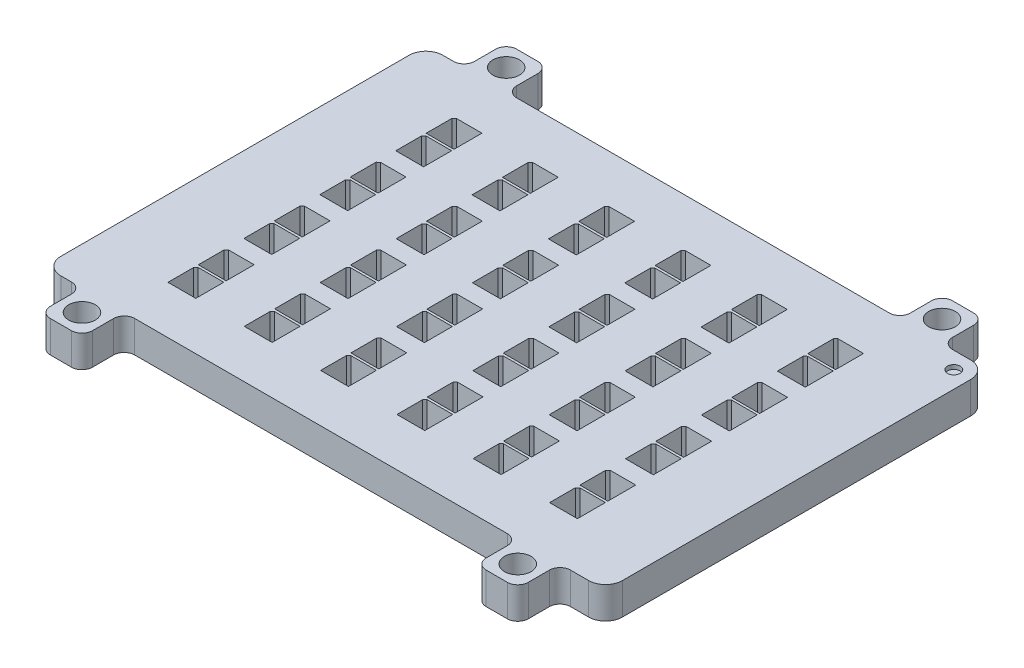
SolidWorks part; units mm, degrees
ref_plane "Front Plane" through (0, 0, 0) normal (0, 0, 1) x (1, 0, 0)
ref_plane "Top Plane" through (0, 0, 0) normal (0, 1, 0) x (1, 0, 0)
ref_plane "Right Plane" through (0, 0, 0) normal (1, 0, 0) x (0, 0, -1)
sketch "Sketch1" plane through (0, 0, 0) normal (0, 1, 0) x (1, 0, 0)
  line L1 (0, 0) -> (157.864, 0)
  line L2 (0, 0) -> (0, -90.551)
  line L3 (0, -90.551) -> (157.864, -90.551)
  line L4 (157.864, 0) -> (157.864, -90.551)
  dimension "D1" = 157.864
  dimension "D2" = 90.551
extrude "Boss-Extrude1" add sketch "Sketch1" along normal blind 24.5
sketch "Sketch39" plane through (0, 24.5, 0) normal (0, 1, 0) x (1, 0, 0)
  line L0 (37.0058, -18.5555) -> (30.949, -18.5555)
  line L1 (30.949, -18.5555) -> (30.4082, -19.0884)
  line L2 (30.4082, -19.0884) -> (30.4082, -25.1854)
  line L3 (30.4082, -25.1854) -> (37.0058, -25.1854)
  line L4 (37.0058, -18.5555) -> (37.0058, -25.1854)
  line L5 (30.4082, -25.1854) -> (37.0058, -18.5555) construction
  line L6 (55.0958, -11.3656) -> (49.039, -11.3656)
  line L7 (49.039, -11.3656) -> (48.4982, -11.8986)
  line L8 (48.4982, -11.8986) -> (48.4982, -17.9955)
  line L9 (48.4982, -17.9955) -> (55.0958, -17.9955)
  line L10 (55.0958, -11.3656) -> (55.0958, -17.9955)
  line L11 (48.4982, -17.9955) -> (55.0958, -11.3656) construction
  line L12 (73.1858, -11.3656) -> (67.129, -11.3656)
  line L13 (67.129, -11.3656) -> (66.5882, -11.8986)
  line L14 (66.5882, -11.8986) -> (66.5882, -17.9955)
  line L15 (66.5882, -17.9955) -> (73.1858, -17.9955)
  line L16 (73.1858, -11.3656) -> (73.1858, -17.9955)
  line L17 (66.5882, -17.9955) -> (73.1858, -11.3656) construction
  line L18 (91.2758, -11.3656) -> (85.219, -11.3656)
  line L19 (85.219, -11.3656) -> (84.6782, -11.8986)
  line L20 (84.6782, -11.8986) -> (84.6782, -17.9955)
  line L21 (84.6782, -17.9955) -> (91.2758, -17.9955)
  line L22 (91.2758, -11.3656) -> (91.2758, -17.9955)
  line L23 (84.6782, -17.9955) -> (91.2758, -11.3656) construction
  line L24 (109.3658, -11.3656) -> (103.309, -11.3656)
  line L25 (103.309, -11.3656) -> (102.7682, -11.8986)
  line L26 (102.7682, -11.8986) -> (102.7682, -17.9955)
  line L27 (102.7682, -17.9955) -> (109.3658, -17.9955)
  line L28 (109.3658, -11.3656) -> (109.3658, -17.9955)
  line L29 (102.7682, -17.9955) -> (109.3658, -11.3656) construction
  line L30 (127.4558, -11.3656) -> (121.399, -11.3656)
  line L31 (121.399, -11.3656) -> (120.8582, -11.8986)
  line L32 (120.8582, -11.8986) -> (120.8582, -17.9955)
  line L33 (120.8582, -17.9955) -> (127.4558, -17.9955)
  line L34 (127.4558, -11.3656) -> (127.4558, -17.9955)
  line L35 (120.8582, -17.9955) -> (127.4558, -11.3656) construction
  line L36 (55.0958, -29.3656) -> (49.039, -29.3656)
  line L37 (49.039, -29.3656) -> (48.4982, -29.8986)
  line L38 (48.4982, -29.8986) -> (48.4982, -35.9955)
  line L39 (48.4982, -35.9955) -> (55.0958, -35.9955)
  line L40 (55.0958, -29.3656) -> (55.0958, -35.9955)
  line L41 (48.4982, -35.9955) -> (55.0958, -29.3656) construction
  line L42 (73.1858, -29.3656) -> (67.129, -29.3656)
  line L43 (67.129, -29.3656) -> (66.5882, -29.8986)
  line L44 (66.5882, -29.8986) -> (66.5882, -35.9955)
  line L45 (66.5882, -35.9955) -> (73.1858, -35.9955)
  line L46 (73.1858, -29.3656) -> (73.1858, -35.9955)
  line L47 (66.5882, -35.9955) -> (73.1858, -29.3656) construction
  line L48 (91.2758, -29.3656) -> (85.219, -29.3656)
  line L49 (85.219, -29.3656) -> (84.6782, -29.8986)
  line L50 (84.6782, -29.8986) -> (84.6782, -35.9955)
  line L51 (84.6782, -35.9955) -> (91.2758, -35.9955)
  line L52 (91.2758, -29.3656) -> (91.2758, -35.9955)
  line L53 (84.6782, -35.9955) -> (91.2758, -29.3656) construction
  line L54 (109.3658, -29.3656) -> (103.309, -29.3656)
  line L55 (103.309, -29.3656) -> (102.7682, -29.8986)
  line L56 (102.7682, -29.8986) -> (102.7682, -35.9955)
  line L57 (102.7682, -35.9955) -> (109.3658, -35.9955)
  line L58 (109.3658, -29.3656) -> (109.3658, -35.9955)
  line L59 (102.7682, -35.9955) -> (109.3658, -29.3656) construction
  line L60 (127.4558, -29.3656) -> (121.399, -29.3656)
  line L61 (121.399, -29.3656) -> (120.8582, -29.8986)
  line L62 (120.8582, -29.8986) -> (120.8582, -35.9955)
  line L63 (120.8582, -35.9955) -> (127.4558, -35.9955)
  line L64 (127.4558, -29.3656) -> (127.4558, -35.9955)
  line L65 (120.8582, -35.9955) -> (127.4558, -29.3656) construction
  line L66 (55.0958, -47.3656) -> (49.039, -47.3656)
  line L67 (49.039, -47.3656) -> (48.4982, -47.8986)
  line L68 (48.4982, -47.8986) -> (48.4982, -53.9955)
  line L69 (48.4982, -53.9955) -> (55.0958, -53.9955)
  line L70 (55.0958, -47.3656) -> (55.0958, -53.9955)
  line L71 (48.4982, -53.9955) -> (55.0958, -47.3656) construction
  line L72 (73.1858, -47.3656) -> (67.129, -47.3656)
  line L73 (67.129, -47.3656) -> (66.5882, -47.8986)
  line L74 (66.5882, -47.8986) -> (66.5882, -53.9955)
  line L75 (66.5882, -53.9955) -> (73.1858, -53.9955)
  line L76 (73.1858, -47.3656) -> (73.1858, -53.9955)
  line L77 (66.5882, -53.9955) -> (73.1858, -47.3656) construction
  line L78 (91.2758, -47.3656) -> (85.219, -47.3656)
  line L79 (85.219, -47.3656) -> (84.6782, -47.8986)
  line L80 (84.6782, -47.8986) -> (84.6782, -53.9955)
  line L81 (84.6782, -53.9955) -> (91.2758, -53.9955)
  line L82 (91.2758, -47.3656) -> (91.2758, -53.9955)
  line L83 (84.6782, -53.9955) -> (91.2758, -47.3656) construction
  line L84 (109.3658, -47.3656) -> (103.309, -47.3656)
  line L85 (103.309, -47.3656) -> (102.7682, -47.8986)
  line L86 (102.7682, -47.8986) -> (102.7682, -53.9955)
  line L87 (102.7682, -53.9955) -> (109.3658, -53.9955)
  line L88 (109.3658, -47.3656) -> (109.3658, -53.9955)
  line L89 (102.7682, -53.9955) -> (109.3658, -47.3656) construction
  line L90 (127.4558, -47.3656) -> (121.399, -47.3656)
  line L91 (121.399, -47.3656) -> (120.8582, -47.8986)
  line L92 (120.8582, -47.8986) -> (120.8582, -53.9955)
  line L93 (120.8582, -53.9955) -> (127.4558, -53.9955)
  line L94 (127.4558, -47.3656) -> (127.4558, -53.9955)
  line L95 (120.8582, -53.9955) -> (127.4558, -47.3656) construction
  line L96 (55.0958, -65.3656) -> (49.039, -65.3656)
  line L97 (49.039, -65.3656) -> (48.4982, -65.8986)
  line L98 (48.4982, -65.8986) -> (48.4982, -71.9955)
  line L99 (48.4982, -71.9955) -> (55.0958, -71.9955)
  line L100 (55.0958, -65.3656) -> (55.0958, -71.9955)
  line L101 (48.4982, -71.9955) -> (55.0958, -65.3656) construction
  line L102 (73.1858, -65.3656) -> (67.129, -65.3656)
  line L103 (67.129, -65.3656) -> (66.5882, -65.8986)
  line L104 (66.5882, -65.8986) -> (66.5882, -71.9955)
  line L105 (66.5882, -71.9955) -> (73.1858, -71.9955)
  line L106 (73.1858, -65.3656) -> (73.1858, -71.9955)
  line L107 (66.5882, -71.9955) -> (73.1858, -65.3656) construction
  line L108 (91.2758, -65.3656) -> (85.219, -65.3656)
  line L109 (85.219, -65.3656) -> (84.6782, -65.8986)
  line L110 (84.6782, -65.8986) -> (84.6782, -71.9955)
  line L111 (84.6782, -71.9955) -> (91.2758, -71.9955)
  line L112 (91.2758, -65.3656) -> (91.2758, -71.9955)
  line L113 (84.6782, -71.9955) -> (91.2758, -65.3656) construction
  line L114 (109.3658, -65.3656) -> (103.309, -65.3656)
  line L115 (103.309, -65.3656) -> (102.7682, -65.8986)
  line L116 (102.7682, -65.8986) -> (102.7682, -71.9955)
  line L117 (102.7682, -71.9955) -> (109.3658, -71.9955)
  line L118 (109.3658, -65.3656) -> (109.3658, -71.9955)
  line L119 (102.7682, -71.9955) -> (109.3658, -65.3656) construction
  line L120 (127.4558, -65.3656) -> (121.399, -65.3656)
  line L121 (121.399, -65.3656) -> (120.8582, -65.8986)
  line L122 (120.8582, -65.8986) -> (120.8582, -71.9955)
  line L123 (120.8582, -71.9955) -> (127.4558, -71.9955)
  line L124 (127.4558, -65.3656) -> (127.4558, -71.9955)
  line L125 (120.8582, -71.9955) -> (127.4558, -65.3656) construction
  line L126 (37.0058, -29.3656) -> (30.949, -29.3656)
  line L127 (30.949, -29.3656) -> (30.4082, -29.8986)
  line L128 (30.4082, -29.8986) -> (30.4082, -35.9955)
  line L129 (30.4082, -35.9955) -> (37.0058, -35.9955)
  line L130 (37.0058, -29.3656) -> (37.0058, -35.9955)
  line L131 (30.4082, -35.9955) -> (37.0058, -29.3656) construction
  line L132 (37.0058, -47.3656) -> (30.949, -47.3656)
  line L133 (30.949, -47.3656) -> (30.4082, -47.8986)
  line L134 (30.4082, -47.8986) -> (30.4082, -53.9955)
  line L135 (30.4082, -53.9955) -> (37.0058, -53.9955)
  line L136 (37.0058, -47.3656) -> (37.0058, -53.9955)
  line L137 (30.4082, -53.9955) -> (37.0058, -47.3656) construction
  line L138 (37.0058, -65.3656) -> (30.949, -65.3656)
  line L139 (30.949, -65.3656) -> (30.4082, -65.8986)
  line L140 (30.4082, -65.8986) -> (30.4082, -71.9955)
  line L141 (30.4082, -71.9955) -> (37.0058, -71.9955)
  line L142 (37.0058, -65.3656) -> (37.0058, -71.9955)
  line L143 (30.4082, -71.9955) -> (37.0058, -65.3656) construction
  line L144 (37.0058, -11.3656) -> (30.949, -11.3656)
  line L145 (30.949, -11.3656) -> (30.4082, -11.8986)
  line L146 (30.4082, -11.8986) -> (30.4082, -17.9955)
  line L147 (30.4082, -17.9955) -> (37.0058, -17.9955)
  line L148 (37.0058, -11.3656) -> (37.0058, -17.9955)
  line L149 (30.4082, -17.9955) -> (37.0058, -11.3656) construction
  line L150 (48.4982, -25.1854) -> (55.0958, -25.1854)
  line L151 (55.0958, -18.5555) -> (55.0958, -25.1854)
  line L152 (55.0958, -18.5555) -> (49.039, -18.5555)
  line L153 (49.039, -18.5555) -> (48.4982, -19.0884)
  line L154 (48.4982, -19.0884) -> (48.4982, -25.1854)
  line L155 (48.4982, -25.1854) -> (55.0958, -18.5555) construction
  line L156 (66.5882, -25.1854) -> (73.1858, -25.1854)
  line L157 (73.1858, -18.5555) -> (73.1858, -25.1854)
  line L158 (73.1858, -18.5555) -> (67.129, -18.5555)
  line L159 (67.129, -18.5555) -> (66.5882, -19.0884)
  line L160 (66.5882, -19.0884) -> (66.5882, -25.1854)
  line L161 (66.5882, -25.1854) -> (73.1858, -18.5555) construction
  line L162 (84.6782, -25.1854) -> (91.2758, -25.1854)
  line L163 (91.2758, -18.5555) -> (91.2758, -25.1854)
  line L164 (91.2758, -18.5555) -> (85.219, -18.5555)
  line L165 (85.219, -18.5555) -> (84.6782, -19.0884)
  line L166 (84.6782, -19.0884) -> (84.6782, -25.1854)
  line L167 (84.6782, -25.1854) -> (91.2758, -18.5555) construction
  line L168 (102.7682, -25.1854) -> (109.3658, -25.1854)
  line L169 (109.3658, -18.5555) -> (109.3658, -25.1854)
  line L170 (109.3658, -18.5555) -> (103.309, -18.5555)
  line L171 (103.309, -18.5555) -> (102.7682, -19.0884)
  line L172 (102.7682, -19.0884) -> (102.7682, -25.1854)
  line L173 (102.7682, -25.1854) -> (109.3658, -18.5555) construction
  line L174 (120.8582, -25.1854) -> (127.4558, -25.1854)
  line L175 (127.4558, -18.5555) -> (127.4558, -25.1854)
  line L176 (127.4558, -18.5555) -> (121.399, -18.5555)
  line L177 (121.399, -18.5555) -> (120.8582, -19.0884)
  line L178 (120.8582, -19.0884) -> (120.8582, -25.1854)
  line L179 (120.8582, -25.1854) -> (127.4558, -18.5555) construction
  line L180 (48.4982, -43.1854) -> (55.0958, -43.1854)
  line L181 (55.0958, -36.5555) -> (55.0958, -43.1854)
  line L182 (55.0958, -36.5555) -> (49.039, -36.5555)
  line L183 (49.039, -36.5555) -> (48.4982, -37.0884)
  line L184 (48.4982, -37.0884) -> (48.4982, -43.1854)
  line L185 (48.4982, -43.1854) -> (55.0958, -36.5555) construction
  line L186 (66.5882, -43.1854) -> (73.1858, -43.1854)
  line L187 (73.1858, -36.5555) -> (73.1858, -43.1854)
  line L188 (73.1858, -36.5555) -> (67.129, -36.5555)
  line L189 (67.129, -36.5555) -> (66.5882, -37.0884)
  line L190 (66.5882, -37.0884) -> (66.5882, -43.1854)
  line L191 (66.5882, -43.1854) -> (73.1858, -36.5555) construction
  line L192 (84.6782, -43.1854) -> (91.2758, -43.1854)
  line L193 (91.2758, -36.5555) -> (91.2758, -43.1854)
  line L194 (91.2758, -36.5555) -> (85.219, -36.5555)
  line L195 (85.219, -36.5555) -> (84.6782, -37.0884)
  line L196 (84.6782, -37.0884) -> (84.6782, -43.1854)
  line L197 (84.6782, -43.1854) -> (91.2758, -36.5555) construction
  line L198 (102.7682, -43.1854) -> (109.3658, -43.1854)
  line L199 (109.3658, -36.5555) -> (109.3658, -43.1854)
  line L200 (109.3658, -36.5555) -> (103.309, -36.5555)
  line L201 (103.309, -36.5555) -> (102.7682, -37.0884)
  line L202 (102.7682, -37.0884) -> (102.7682, -43.1854)
  line L203 (102.7682, -43.1854) -> (109.3658, -36.5555) construction
  line L204 (120.8582, -43.1854) -> (127.4558, -43.1854)
  line L205 (127.4558, -36.5555) -> (127.4558, -43.1854)
  line L206 (127.4558, -36.5555) -> (121.399, -36.5555)
  line L207 (121.399, -36.5555) -> (120.8582, -37.0884)
  line L208 (120.8582, -37.0884) -> (120.8582, -43.1854)
  line L209 (120.8582, -43.1854) -> (127.4558, -36.5555) construction
  line L210 (48.4982, -61.1854) -> (55.0958, -61.1854)
  line L211 (55.0958, -54.5555) -> (55.0958, -61.1854)
  line L212 (55.0958, -54.5555) -> (49.039, -54.5555)
  line L213 (49.039, -54.5555) -> (48.4982, -55.0884)
  line L214 (48.4982, -55.0884) -> (48.4982, -61.1854)
  line L215 (48.4982, -61.1854) -> (55.0958, -54.5555) construction
  line L216 (66.5882, -61.1854) -> (73.1858, -61.1854)
  line L217 (73.1858, -54.5555) -> (73.1858, -61.1854)
  line L218 (73.1858, -54.5555) -> (67.129, -54.5555)
  line L219 (67.129, -54.5555) -> (66.5882, -55.0884)
  line L220 (66.5882, -55.0884) -> (66.5882, -61.1854)
  line L221 (66.5882, -61.1854) -> (73.1858, -54.5555) construction
  line L222 (84.6782, -61.1854) -> (91.2758, -61.1854)
  line L223 (91.2758, -54.5555) -> (91.2758, -61.1854)
  line L224 (91.2758, -54.5555) -> (85.219, -54.5555)
  line L225 (85.219, -54.5555) -> (84.6782, -55.0884)
  line L226 (84.6782, -55.0884) -> (84.6782, -61.1854)
  line L227 (84.6782, -61.1854) -> (91.2758, -54.5555) construction
  line L228 (102.7682, -61.1854) -> (109.3658, -61.1854)
  line L229 (109.3658, -54.5555) -> (109.3658, -61.1854)
  line L230 (109.3658, -54.5555) -> (103.309, -54.5555)
  line L231 (103.309, -54.5555) -> (102.7682, -55.0884)
  line L232 (102.7682, -55.0884) -> (102.7682, -61.1854)
  line L233 (102.7682, -61.1854) -> (109.3658, -54.5555) construction
  line L234 (120.8582, -61.1854) -> (127.4558, -61.1854)
  line L235 (127.4558, -54.5555) -> (127.4558, -61.1854)
  line L236 (127.4558, -54.5555) -> (121.399, -54.5555)
  line L237 (121.399, -54.5555) -> (120.8582, -55.0884)
  line L238 (120.8582, -55.0884) -> (120.8582, -61.1854)
  line L239 (120.8582, -61.1854) -> (127.4558, -54.5555) construction
  line L240 (48.4982, -79.1854) -> (55.0958, -79.1854)
  line L241 (55.0958, -72.5555) -> (55.0958, -79.1854)
  line L242 (55.0958, -72.5555) -> (49.039, -72.5555)
  line L243 (49.039, -72.5555) -> (48.4982, -73.0884)
  line L244 (48.4982, -73.0884) -> (48.4982, -79.1854)
  line L245 (48.4982, -79.1854) -> (55.0958, -72.5555) construction
  line L246 (66.5882, -79.1854) -> (73.1858, -79.1854)
  line L247 (73.1858, -72.5555) -> (73.1858, -79.1854)
  line L248 (73.1858, -72.5555) -> (67.129, -72.5555)
  line L249 (67.129, -72.5555) -> (66.5882, -73.0884)
  line L250 (66.5882, -73.0884) -> (66.5882, -79.1854)
  line L251 (66.5882, -79.1854) -> (73.1858, -72.5555) construction
  line L252 (84.6782, -79.1854) -> (91.2758, -79.1854)
  line L253 (91.2758, -72.5555) -> (91.2758, -79.1854)
  line L254 (91.2758, -72.5555) -> (85.219, -72.5555)
  line L255 (85.219, -72.5555) -> (84.6782, -73.0884)
  line L256 (84.6782, -73.0884) -> (84.6782, -79.1854)
  line L257 (84.6782, -79.1854) -> (91.2758, -72.5555) construction
  line L258 (102.7682, -79.1854) -> (109.3658, -79.1854)
  line L259 (109.3658, -72.5555) -> (109.3658, -79.1854)
  line L260 (109.3658, -72.5555) -> (103.309, -72.5555)
  line L261 (103.309, -72.5555) -> (102.7682, -73.0884)
  line L262 (102.7682, -73.0884) -> (102.7682, -79.1854)
  line L263 (102.7682, -79.1854) -> (109.3658, -72.5555) construction
  line L264 (120.8582, -79.1854) -> (127.4558, -79.1854)
  line L265 (127.4558, -72.5555) -> (127.4558, -79.1854)
  line L266 (127.4558, -72.5555) -> (121.399, -72.5555)
  line L267 (121.399, -72.5555) -> (120.8582, -73.0884)
  line L268 (120.8582, -73.0884) -> (120.8582, -79.1854)
  line L269 (120.8582, -79.1854) -> (127.4558, -72.5555) construction
  line L270 (30.4082, -43.1854) -> (37.0058, -43.1854)
  line L271 (37.0058, -36.5555) -> (37.0058, -43.1854)
  line L272 (37.0058, -36.5555) -> (30.949, -36.5555)
  line L273 (30.949, -36.5555) -> (30.4082, -37.0884)
  line L274 (30.4082, -37.0884) -> (30.4082, -43.1854)
  line L275 (30.4082, -43.1854) -> (37.0058, -36.5555) construction
  line L276 (30.4082, -61.1854) -> (37.0058, -61.1854)
  line L277 (37.0058, -54.5555) -> (37.0058, -61.1854)
  line L278 (37.0058, -54.5555) -> (30.949, -54.5555)
  line L279 (30.949, -54.5555) -> (30.4082, -55.0884)
  line L280 (30.4082, -55.0884) -> (30.4082, -61.1854)
  line L281 (30.4082, -61.1854) -> (37.0058, -54.5555) construction
  line L282 (30.4082, -79.1854) -> (37.0058, -79.1854)
  line L283 (37.0058, -72.5555) -> (37.0058, -79.1854)
  line L284 (37.0058, -72.5555) -> (30.949, -72.5555)
  line L285 (30.949, -72.5555) -> (30.4082, -73.0884)
  line L286 (30.4082, -73.0884) -> (30.4082, -79.1854)
  line L287 (30.4082, -79.1854) -> (37.0058, -72.5555) construction
  line L288 (127.4558, -25.1854) -> (157.864, -25.1854) construction
  line L289 (30.4082, -79.1854) -> (0, -79.1854) construction
  line L290 (0, 0) -> (0, -90.551) construction
  line L291 (30.4082, -79.1854) -> (30.4082, -90.551) construction
  line L292 (0, -90.551) -> (157.864, -90.551) construction
  line L293 (127.4558, -11.3656) -> (127.4558, 0) construction
  line L294 (157.864, 0) -> (0, 0) construction
  line L295 (127.4558, -11.3656) -> (157.864, -11.3656) construction
  line L296 (157.864, -90.551) -> (157.864, 0) construction
  point P0 (33.707, -21.8704)
  point P2 (33.707, -14.6806)
  point P12 (51.797, -14.6806)
  point P18 (69.887, -14.6806)
  point P24 (87.977, -14.6806)
  point P30 (106.067, -14.6806)
  point P36 (124.157, -14.6806)
  point P42 (51.797, -32.6806)
  point P48 (69.887, -32.6806)
  point P54 (87.977, -32.6806)
  point P60 (106.067, -32.6806)
  point P66 (124.157, -32.6806)
  point P72 (51.797, -50.6806)
  point P78 (69.887, -50.6806)
  point P84 (87.977, -50.6806)
  point P90 (106.067, -50.6806)
  point P96 (124.157, -50.6806)
  point P102 (51.797, -68.6806)
  point P108 (69.887, -68.6806)
  point P114 (87.977, -68.6806)
  point P120 (106.067, -68.6806)
  point P126 (124.157, -68.6806)
  point P132 (33.707, -32.6806)
  point P138 (33.707, -50.6806)
  point P144 (33.707, -68.6806)
  point P153 (51.797, -21.8704)
  point P159 (69.887, -21.8704)
  point P165 (87.977, -21.8704)
  point P171 (106.067, -21.8704)
  point P177 (124.157, -21.8704)
  point P183 (51.797, -39.8704)
  point P189 (69.887, -39.8704)
  point P195 (87.977, -39.8704)
  point P201 (106.067, -39.8704)
  point P207 (124.157, -39.8704)
  point P213 (51.797, -57.8704)
  point P219 (69.887, -57.8704)
  point P225 (87.977, -57.8704)
  point P231 (106.067, -57.8704)
  point P237 (124.157, -57.8704)
  point P243 (51.797, -75.8704)
  point P249 (69.887, -75.8704)
  point P255 (87.977, -75.8704)
  point P261 (106.067, -75.8704)
  point P267 (124.157, -75.8704)
  point P273 (33.707, -39.8704)
  point P279 (33.707, -57.8704)
  point P285 (33.707, -75.8704)
  dimension "D2" = 6.0568
  dimension "D3" = 6.0969
  dimension "D4" = 6.5976
  dimension "D5" = 6.6299
  dimension "D6" = 0.7593
  dimension "D7" = 6
  dimension "D8" = 4
  dimension "D9" = 0.56
  dimension "D10" = 6.0568
  dimension "D11" = 6.0969
  dimension "D12" = 6.6299
  dimension "D13" = 6.5976
  dimension "D14" = 0.7593
  dimension "D15" = 6
  dimension "D16" = 4
extrude "Cut-Extrude30" cut sketch "Sketch39" against normal up to surface (24.5 mm away) up to face at (78.932, 0, 45.2755)
sketch "Sketch7" plane through (0, 0, 0) normal (0, -1, 0) x (1, 0, 0)
  line L0 (124.157, 18.2755) -> (157.864, 18.2755) construction
  line L1 (157.864, 90.551) -> (157.864, 0) construction
  line L2 (124.157, 18.2755) -> (124.157, 0) construction
  line L3 (157.864, 0) -> (0, 0) construction
  line L4 (33.707, 18.2755) -> (0, 18.2755) construction
  line L5 (0, 0) -> (0, 90.551) construction
  line L6 (33.707, 72.2755) -> (33.707, 90.551) construction
  line L7 (0, 90.551) -> (157.864, 90.551) construction
  line L8 (33.707, 72.2755) -> (33.707, 90.551) construction
  circle A0 centre (33.707, 72.2755) radius 7.75
  circle A2 centre (51.797, 72.2755) radius 7.75
  circle A3 centre (69.887, 72.2755) radius 7.75
  circle A4 centre (87.977, 72.2755) radius 7.75
  circle A5 centre (106.067, 72.2755) radius 7.75
  circle A6 centre (124.157, 72.2755) radius 7.75
  circle A7 centre (51.797, 54.2755) radius 7.75
  circle A8 centre (69.887, 54.2755) radius 7.75
  circle A9 centre (87.977, 54.2755) radius 7.75
  circle A10 centre (106.067, 54.2755) radius 7.75
  circle A11 centre (124.157, 54.2755) radius 7.75
  circle A12 centre (51.797, 36.2755) radius 7.75
  circle A13 centre (69.887, 36.2755) radius 7.75
  circle A14 centre (87.977, 36.2755) radius 7.75
  circle A15 centre (106.067, 36.2755) radius 7.75
  circle A16 centre (124.157, 36.2755) radius 7.75
  circle A17 centre (51.797, 18.2755) radius 7.75
  circle A18 centre (69.887, 18.2755) radius 7.75
  circle A19 centre (87.977, 18.2755) radius 7.75
  circle A20 centre (106.067, 18.2755) radius 7.75
  circle A21 centre (124.157, 18.2755) radius 7.75
  circle A22 centre (33.707, 54.2755) radius 7.75
  circle A23 centre (33.707, 36.2755) radius 7.75
  circle A24 centre (33.707, 18.2755) radius 7.75
  dimension "D1" = 15.5
  dimension "D6" = 18
  dimension "D3" = 18.09
  dimension "D4" = 18
  dimension "D5" = 18.09
  dimension "D7" = 6
  dimension "D8" = 4
extrude "Cut-Extrude5" cut sketch "Sketch7" along normal blind 17 from surface at -24.5 starting at face at (33.1554, 24.5, 75.314)
sketch "Sketch23" plane through (0, 24.5, 0) normal (0, 1, 0) x (1, 0, 0)
  line L0 (0, -90.551) -> (157.864, -90.551) construction
  line L1 (143.5751, -88.6374) -> (14.2889, -88.6374)
  line L2 (143.5751, -88.6374) -> (143.5751, -1.9136)
  line L3 (143.5751, -1.9136) -> (14.2889, -1.9136)
  line L4 (14.2889, -88.6374) -> (14.2889, -1.9136)
  line L5 (134.6751, -82.6374) -> (23.1889, -82.6374)
  line L6 (134.6751, -82.6374) -> (134.6751, -7.9136)
  line L7 (134.6751, -7.9136) -> (23.1889, -7.9136)
  line L8 (23.1889, -82.6374) -> (23.1889, -7.9136)
  line L9 (157.864, -90.551) -> (157.864, 0) construction
  line L10 (157.864, 0) -> (0, 0) construction
  line L11 (0, 0) -> (0, -90.551) construction
  point P8 (157.864, -45.2755)
  point P17 (0, -45.2755)
  dimension "D1" = 129.2861
  dimension "D2" = 8.9
  dimension "D3" = 8.9
  dimension "D4" = 6
  dimension "D5" = 6
  dimension "D6" = 14.2889
  dimension "D8" = 1.9136
  dimension "D9" = 86.7238
  dimension "D10" = 1.9136
  dimension "D11" = 14.2889
extrude "Cut-Extrude21" cut sketch "Sketch23" against normal blind 4.5
fillet "Fillet7" radius 1 4 edges at (134.6751, 22.25, 7.9136) (23.1889, 22.25, 7.9136) (23.1889, 22.25, 82.6374) (134.6751, 22.25, 82.6374)
fillet "Fillet8" radius 2.75 4 edges at (143.5751, 22.25, 1.9136) (14.2889, 22.25, 1.9136) (14.2889, 22.25, 88.6374) (143.5751, 22.25, 88.6374)
sketch "Sketch26" plane through (0, 24.5, 0) normal (0, 1, 0) x (1, 0, 0)
  line L1 (18.0889, -82.6374) -> (134.6751, -82.6374)
  line L2 (18.0889, -82.6374) -> (18.0889, -7.9136)
  line L3 (18.0889, -7.9136) -> (134.6751, -7.9136)
  line L4 (134.6751, -82.6374) -> (134.6751, -7.9136)
  dimension "D1" = 0
  dimension "D2" = 0
  dimension "D3" = 1
  dimension "D4" = 0
extrude "Cut-Extrude22" cut sketch "Sketch26" against normal blind 3
sketch "Sketch29" plane through (0, 24.5, 0) normal (0, 1, 0) x (1, 0, 0)
  line L0 (157.864, 0) -> (0, 0) construction
  line L1 (157.864, -90.551) -> (145.4887, -90.551)
  line L2 (157.864, -90.551) -> (157.864, 0)
  line L3 (157.864, 0) -> (145.4887, 0)
  line L4 (145.4887, -90.551) -> (145.4887, 0)
  line L6 (0, -90.551) -> (12.3753, -90.551)
  line L7 (0, -90.551) -> (0, 0)
  line L8 (0, 0) -> (12.3753, 0)
  line L9 (12.3753, -90.551) -> (12.3753, 0)
  dimension "D2" = 1.9136
  dimension "D3" = 1.9136
extrude "Cut-Extrude25" cut sketch "Sketch29" against normal through all
fillet "Fillet9" radius 4 4 edges at (12.3753, 12.25, 90.551) (145.4887, 12.25, 90.551) (145.4887, 12.25, 0) (12.3753, 12.25, 0)
sketch "Sketch30" plane through (0, 0, 0) normal (0, -1, 0) x (1, 0, 0)
  line L0 (141.4887, 0) -> (16.3753, 0) construction
  line L1 (134.6936, 0) -> (124.6936, 0)
  line L2 (134.6936, 0) -> (134.6936, -10)
  line L3 (134.6936, -10) -> (124.6936, -10)
  line L4 (124.6936, 0) -> (124.6936, -10)
  line L5 (16.3753, 90.551) -> (141.4887, 90.551) construction
  line L6 (21.3936, 0) -> (31.3936, 0)
  line L7 (21.3936, 0) -> (21.3936, -10)
  line L8 (21.3936, -10) -> (31.3936, -10)
  line L9 (31.3936, 0) -> (31.3936, -10)
  line L10 (134.6936, 90.551) -> (124.6936, 90.551)
  line L11 (134.6936, 90.551) -> (134.6936, 100.551)
  line L12 (134.6936, 100.551) -> (124.6936, 100.551)
  line L13 (124.6936, 90.551) -> (124.6936, 100.551)
  line L14 (124.6936, -10) -> (31.3936, -10) construction
  line L15 (21.3936, 90.551) -> (31.3936, 90.551)
  line L16 (21.3936, 90.551) -> (21.3936, 100.551)
  line L17 (21.3936, 100.551) -> (31.3936, 100.551)
  line L18 (31.3936, 90.551) -> (31.3936, 100.551)
  line L19 (124.6936, 100.551) -> (31.3936, 100.551) construction
  line L20 (31.3936, -10) -> (21.3936, 0) construction
  line L22 (33.707, 0) -> (31.3936, 0) construction
  line L23 (21.3936, 90.551) -> (16.3753, 90.551) construction
  line L24 (33.707, 72.2755) -> (33.707, 18.2755) construction
  line L25 (33.707, 18.2755) -> (33.707, 0) construction
  line L26 (21.3936, -10) -> (31.3936, 0) construction
  line L27 (33.707, 72.2755) -> (33.707, 90.551) construction
  line L28 (31.3936, 90.551) -> (21.3936, 100.551) construction
  line L29 (21.3936, 90.551) -> (31.3936, 100.551) construction
  point P21 (26.3936, -5)
  point P25 (26.3936, 95.551)
  dimension "D1" = 10
  dimension "D2" = 93.3
  dimension "D3" = 7.3134
  dimension "D4" = 7.3134
extrude "Boss-Extrude2" add sketch "Sketch30" against normal through all
sketch "Sketch31" plane through (0, 24.5, 0) normal (0, 1, 0) x (1, 0, 0)
  line L0 (21.3936, 10) -> (31.3936, 0) construction
  line L1 (31.3936, 0) -> (21.3936, 0) construction
  line L2 (21.3936, 0) -> (31.3936, 10) construction
  line L3 (124.6936, 10) -> (134.6936, 0) construction
  line L4 (134.6936, 0) -> (124.6936, 0) construction
  line L5 (124.6936, 0) -> (134.6936, 10) construction
  line L6 (124.6936, -90.551) -> (134.6936, -100.551) construction
  line L7 (134.6936, -100.551) -> (124.6936, -100.551) construction
  line L8 (124.6936, -100.551) -> (134.6936, -90.551) construction
  line L9 (21.3936, -90.551) -> (31.3936, -100.551) construction
  line L10 (31.3936, -100.551) -> (21.3936, -100.551) construction
  line L11 (21.3936, -100.551) -> (31.3936, -90.551) construction
  circle A0 centre (26.3936, 5) radius 3.15
  circle A1 centre (129.6936, 5) radius 3.15
  circle A2 centre (26.3936, -95.551) radius 3.15
  circle A3 centre (129.6936, -95.551) radius 3.15
  dimension "D1" = 6.3
extrude "Cut-Extrude26" cut sketch "Sketch31" against normal through all
fillet "Fillet10" radius 2.5 16 edges at (21.3936, 12.25, 100.551) (124.6936, 12.25, 100.551) (31.3936, 12.25, 100.551) (134.6936, 12.25, 100.551) (134.6936, 12.25, -10) (124.6936, 12.25, -10) (31.3936, 12.25, -10) (21.3936, 12.25, -10) (21.3936, 12.25, 90.551) (31.3936, 12.25, 90.551) (124.6936, 12.25, 90.551) (134.6936, 12.25, 90.551) (134.6936, 12.25, 0) (124.6936, 12.25, 0) (31.3936, 12.25, 0) (21.3936, 12.25, 0)
sketch "Sketch35" plane through (0, 21.5, 0) normal (0, 1, 0) x (1, 0, 0)
  line L0 (33.707, -54.2755) -> (51.797, -72.2755) construction
  line L1 (51.797, -72.2755) -> (33.707, -72.2755) construction
  line L2 (33.707, -72.2755) -> (51.797, -54.2755) construction
  line L3 (106.067, -18.2755) -> (124.157, -36.2755) construction
  line L4 (124.157, -36.2755) -> (106.067, -36.2755) construction
  line L5 (106.067, -36.2755) -> (124.157, -18.2755) construction
  circle A2 centre (115.112, -27.2755) radius 1.4
  circle A3 centre (42.752, -63.2755) radius 1.4
  dimension "D1" = 2.8
extrude "Boss-Extrude3" add sketch "Sketch35" along normal blind 0.75
sketch "Sketch37" plane through (0, 24.5, 0) normal (0, 1, 0) x (1, 0, 0)
  line L1 (-21.3738, -118.5753) -> (214.6608, -118.5753)
  line L2 (-21.3738, -118.5753) -> (-21.3738, 29.3482)
  line L3 (-21.3738, 29.3482) -> (214.6608, 29.3482)
  line L4 (214.6608, -118.5753) -> (214.6608, 29.3482)
extrude "Cut-Extrude29" cut sketch "Sketch37" against normal blind 4.5
sketch "Sketch36" plane through (0, 0, 0) normal (0, -1, 0) x (1, 0, 0)
  line L0 (23.3443, 83.2148) -> (23.3443, 88.2648) construction
  line L1 (14.5962, 88.2648) -> (143.8803, 88.2648)
  line L2 (14.5962, 88.2648) -> (14.5962, 2.0921)
  line L3 (14.5962, 2.0921) -> (143.8803, 2.0921)
  line L4 (143.8803, 88.2648) -> (143.8803, 2.0921)
  line L5 (23.3443, 83.2148) -> (135.1322, 83.2148)
  line L6 (23.3443, 83.2148) -> (23.3443, 7.142)
  line L7 (23.3443, 7.142) -> (135.1322, 7.142)
  line L8 (135.1322, 83.2148) -> (135.1322, 7.142)
  line L9 (23.3443, 83.2148) -> (14.5962, 83.2148) construction
  line L10 (135.1322, 7.142) -> (143.8803, 7.142) construction
  line L11 (135.1322, 7.142) -> (135.1322, 2.0921) construction
extrude "Cut-Extrude28" [suppressed] cut sketch "Sketch36" against normal blind 17
fillet "Fillet11" [suppressed] radius 4
fillet "Fillet12" [suppressed] radius 4
sketch "Sketch42" [suppressed] plane through (0, 0, 0) normal (0, -1, 0) x (1, 0, 0)
  line L0 (22.1833, 72.1734) -> (22.1833, 18.1834) construction
  line L1 (22.1833, 18.1834) -> (136.2933, 18.1834) construction
  line L2 (136.2933, 18.1834) -> (136.2933, 72.1734) construction
  line L3 (136.2933, 72.1734) -> (22.1833, 72.1734) construction
  line L4 (22.1833, 72.1734) -> (14.5962, 72.1734) construction
  line L5 (14.5962, 84.2648) -> (14.5962, 6.0921) construction
  line L6 (22.1833, 72.1734) -> (22.1833, 88.2648) construction
  line L7 (139.8803, 88.2648) -> (18.5962, 88.2648) construction
  line L8 (136.2933, 72.1734) -> (143.8803, 72.1734) construction
  line L9 (143.8803, 6.0921) -> (143.8803, 84.2648) construction
  line L10 (136.2933, 18.1834) -> (136.2933, 2.0921) construction
  line L11 (18.5962, 2.0921) -> (139.8803, 2.0921) construction
  circle A0 centre (22.1833, 72.1734) radius 3.1
  circle A1 centre (22.1833, 18.1834) radius 3.1
  circle A2 centre (136.2933, 18.1834) radius 3.1
  circle A3 centre (136.2933, 72.1734) radius 3.1
  dimension "D1" = 6.2
  dimension "D2" = 114.11
  dimension "D3" = 53.99
extrude "Cut-Extrude31" [suppressed] cut sketch "Sketch42" against normal blind 2.75
sketch "Sketch43" plane through (0, 20, 0) normal (0, 1, 0) x (1, 0, 0)
  circle A0 centre (140.1936, -3) radius 1
  dimension "D1" = 2
  dimension "D2" = 3
  dimension "D3" = 3
extrude "Cut-Extrude32" cut sketch "Sketch43" against normal blind 1
chamfer "Chamfer1" [suppressed] distance 0.25 angle 45
sketch "Sketch44" plane through (12.3753, 0, 0) normal (-1, 0, 0) x (0, 0, 1)
  line L0 (10.9005, 6.6667) -> (23.4005, 6.6667) construction
  line L1 (23.4005, 6.6667) -> (35.9005, 6.6667) construction
  line L2 (35.9005, 6.6667) -> (48.4005, 6.6667) construction
  line L3 (48.4005, 6.6667) -> (60.9005, 6.6667) construction
  line L4 (60.9005, 6.6667) -> (73.4005, 6.6667) construction
  line L5 (17.1505, 13.3333) -> (29.6505, 13.3333) construction
  line L6 (29.6505, 13.3333) -> (42.1505, 13.3333) construction
  line L7 (42.1505, 13.3333) -> (54.6505, 13.3333) construction
  line L8 (54.6505, 13.3333) -> (67.1505, 13.3333) construction
  line L9 (67.1505, 13.3333) -> (79.6505, 13.3333) construction
  line L10 (10.9005, 6.6667) -> (17.1505, 13.3333) construction
  line L11 (17.1505, 13.3333) -> (23.4005, 6.6667) construction
  line L12 (10.9005, 6.6667) -> (4, 6.6667) construction
  line L13 (4, 20) -> (4, 0) construction
  line L14 (79.6505, 13.3333) -> (86.551, 13.3333) construction
  line L15 (86.551, 0) -> (86.551, 20) construction
  line L16 (17.1505, 13.3333) -> (17.1505, 20) construction
  line L17 (86.551, 20) -> (4, 20) construction
  line L18 (10.9005, 6.6667) -> (10.9005, 0) construction
  line L19 (86.551, 0) -> (4, 0) construction
  line L20 (17.1505, 13.3333) -> (17.1505, 6.6667) construction
  circle A0 centre (10.9005, 6.6667) radius 3
  circle A1 centre (23.4005, 6.6667) radius 3
  circle A2 centre (35.9005, 6.6667) radius 3
  circle A3 centre (48.4005, 6.6667) radius 3
  circle A4 centre (60.9005, 6.6667) radius 3
  circle A5 centre (73.4005, 6.6667) radius 3
  circle A6 centre (17.1505, 13.3333) radius 3
  circle A7 centre (29.6505, 13.3333) radius 3
  circle A8 centre (42.1505, 13.3333) radius 3
  circle A9 centre (54.6505, 13.3333) radius 3
  circle A10 centre (67.1505, 13.3333) radius 3
  circle A11 centre (79.6505, 13.3333) radius 3
  dimension "D1" = 6
  dimension "D2" = 12.5
extrude "Cut-Extrude33" [suppressed] cut sketch "Sketch44" against normal up to surface (2.2209 mm away)
sketch "Sketch45" plane through (0, 0, 90.551) normal (0, 0, 1) x (1, 0, 0)
  line L0 (37.4186, 13.3333) -> (49.9186, 13.3333) construction
  line L1 (49.9186, 13.3333) -> (62.4186, 13.3333) construction
  line L2 (62.4186, 13.3333) -> (74.9186, 13.3333) construction
  line L3 (74.9186, 13.3333) -> (87.4186, 13.3333) construction
  line L4 (87.4186, 13.3333) -> (99.9186, 13.3333) construction
  line L5 (99.9186, 13.3333) -> (112.4186, 13.3333) construction
  line L6 (118.6686, 6.6667) -> (106.1686, 6.6667) construction
  line L7 (106.1686, 6.6667) -> (93.6686, 6.6667) construction
  line L8 (93.6686, 6.6667) -> (81.1686, 6.6667) construction
  line L9 (81.1686, 6.6667) -> (68.6686, 6.6667) construction
  line L10 (68.6686, 6.6667) -> (56.1686, 6.6667) construction
  line L11 (56.1686, 6.6667) -> (43.6686, 6.6667) construction
  line L12 (43.6686, 6.6667) -> (37.4186, 13.3333) construction
  line L13 (37.4186, 13.3333) -> (49.9186, 13.3333) construction
  line L14 (49.9186, 13.3333) -> (43.6686, 6.6667) construction
  line L15 (37.4186, 13.3333) -> (37.4186, 20) construction
  line L16 (122.1936, 20) -> (33.8936, 20) construction
  line L17 (43.6686, 6.6667) -> (43.6686, 0) construction
  line L18 (33.8936, 0) -> (122.1936, 0) construction
  line L19 (37.4186, 13.3333) -> (33.8936, 13.3333) construction
  line L20 (33.8936, 20) -> (33.8936, 0) construction
  line L21 (118.6686, 6.6667) -> (122.1936, 6.6667) construction
  line L22 (122.1936, 0) -> (122.1936, 20) construction
  line L23 (43.6686, 6.6667) -> (43.6686, 13.3333) construction
  circle A0 centre (37.4186, 13.3333) radius 3
  circle A1 centre (49.9186, 13.3333) radius 3
  circle A2 centre (62.4186, 13.3333) radius 3
  circle A3 centre (74.9186, 13.3333) radius 3
  circle A4 centre (87.4186, 13.3333) radius 3
  circle A5 centre (99.9186, 13.3333) radius 3
  circle A6 centre (112.4186, 13.3333) radius 3
  circle A7 centre (43.6686, 6.6667) radius 3
  circle A8 centre (56.1686, 6.6667) radius 3
  circle A9 centre (68.6686, 6.6667) radius 3
  circle A10 centre (81.1686, 6.6667) radius 3
  circle A11 centre (93.6686, 6.6667) radius 3
  circle A12 centre (106.1686, 6.6667) radius 3
  circle A13 centre (118.6686, 6.6667) radius 3
  dimension "D1" = 6
  dimension "D2" = 12.5
extrude "Cut-Extrude34" [suppressed] cut sketch "Sketch45" against normal up to surface (2.2862 mm away)
sketch "Sketch46" plane through (145.4887, 0, 0) normal (1, 0, 0) x (0, 0, -1)
  line L0 (-79.6505, 13.3333) -> (-67.1505, 13.3333) construction
  line L1 (-67.1505, 13.3333) -> (-54.6505, 13.3333) construction
  line L2 (-54.6505, 13.3333) -> (-42.1505, 13.3333) construction
  line L3 (-42.1505, 13.3333) -> (-29.6505, 13.3333) construction
  line L4 (-29.6505, 13.3333) -> (-17.1505, 13.3333) construction
  line L5 (-73.4005, 6.6667) -> (-60.9005, 6.6667) construction
  line L6 (-60.9005, 6.6667) -> (-48.4005, 6.6667) construction
  line L7 (-48.4005, 6.6667) -> (-35.9005, 6.6667) construction
  line L8 (-35.9005, 6.6667) -> (-23.4005, 6.6667) construction
  line L9 (-23.4005, 6.6667) -> (-10.9005, 6.6667) construction
  line L10 (-67.1505, 13.3333) -> (-79.6505, 13.3333) construction
  line L11 (-79.6505, 13.3333) -> (-73.4005, 6.6667) construction
  line L12 (-73.4005, 6.6667) -> (-67.1505, 13.3333) construction
  line L13 (-79.6505, 13.3333) -> (-79.6505, 20) construction
  line L14 (-4, 20) -> (-86.551, 20) construction
  line L15 (-73.4005, 6.6667) -> (-73.4005, 0) construction
  line L16 (-4, 0) -> (-86.551, 0) construction
  line L17 (-79.6505, 13.3333) -> (-86.551, 13.3333) construction
  line L18 (-86.551, 20) -> (-86.551, 0) construction
  line L19 (-10.9005, 6.6667) -> (-4, 6.6667) construction
  line L20 (-4, 0) -> (-4, 20) construction
  line L21 (-73.4005, 6.6667) -> (-73.4005, 13.3333) construction
  circle A0 centre (-79.6505, 13.3333) radius 3
  circle A1 centre (-67.1505, 13.3333) radius 3
  circle A2 centre (-54.6505, 13.3333) radius 3
  circle A3 centre (-42.1505, 13.3333) radius 3
  circle A4 centre (-29.6505, 13.3333) radius 3
  circle A5 centre (-73.4005, 6.6667) radius 3
  circle A6 centre (-17.1505, 13.3333) radius 3
  circle A7 centre (-60.9005, 6.6667) radius 3
  circle A8 centre (-48.4005, 6.6667) radius 3
  circle A9 centre (-35.9005, 6.6667) radius 3
  circle A10 centre (-23.4005, 6.6667) radius 3
  circle A11 centre (-10.9005, 6.6667) radius 3
  dimension "D1" = 6
  dimension "D2" = 12.5
extrude "Cut-Extrude35" [suppressed] cut sketch "Sketch46" against normal up to surface (1.6084 mm away)
sketch "Sketch47" plane through (0, 0, 0) normal (0, 0, -1) x (-1, 0, 0)
  line L0 (-118.6686, 13.3333) -> (-106.1686, 13.3333) construction
  line L1 (-106.1686, 13.3333) -> (-93.6686, 13.3333) construction
  line L2 (-93.6686, 13.3333) -> (-81.1686, 13.3333) construction
  line L3 (-81.1686, 13.3333) -> (-68.6686, 13.3333) construction
  line L4 (-68.6686, 13.3333) -> (-56.1686, 13.3333) construction
  line L5 (-56.1686, 13.3333) -> (-43.6686, 13.3333) construction
  line L7 (-112.4186, 6.6667) -> (-99.9186, 6.6667) construction
  line L8 (-99.9186, 6.6667) -> (-87.4186, 6.6667) construction
  line L9 (-87.4186, 6.6667) -> (-74.9186, 6.6667) construction
  line L10 (-74.9186, 6.6667) -> (-62.4186, 6.6667) construction
  line L11 (-62.4186, 6.6667) -> (-49.9186, 6.6667) construction
  line L12 (-49.9186, 6.6667) -> (-37.4186, 6.6667) construction
  line L13 (-118.6686, 13.3333) -> (-106.1686, 13.3333) construction
  line L14 (-106.1686, 13.3333) -> (-112.4186, 6.6667) construction
  line L15 (-112.4186, 6.6667) -> (-118.6686, 13.3333) construction
  line L16 (-112.4186, 6.6667) -> (-112.4186, 13.3333) construction
  line L17 (-118.6686, 13.3333) -> (-118.6686, 20) construction
  line L18 (-33.8936, 20) -> (-122.1936, 20) construction
  line L19 (-112.4186, 6.6667) -> (-112.4186, 0) construction
  line L20 (-122.1936, 0) -> (-33.8936, 0) construction
  line L21 (-118.6686, 13.3333) -> (-122.1936, 13.3333) construction
  line L22 (-122.1936, 20) -> (-122.1936, 0) construction
  line L23 (-37.4186, 6.6667) -> (-33.8936, 6.6667) construction
  line L24 (-33.8936, 0) -> (-33.8936, 20) construction
  circle A0 centre (-118.6686, 13.3333) radius 3
  circle A1 centre (-43.6686, 13.3333) radius 3
  circle A2 centre (-81.1686, 13.3333) radius 3
  circle A3 centre (-68.6686, 13.3333) radius 3
  circle A4 centre (-56.1686, 13.3333) radius 3
  circle A6 centre (-93.6686, 13.3333) radius 3
  circle A7 centre (-106.1686, 13.3333) radius 3
  circle A8 centre (-112.4186, 6.6667) radius 3
  circle A9 centre (-99.9186, 6.6667) radius 3
  circle A10 centre (-87.4186, 6.6667) radius 3
  circle A11 centre (-74.9186, 6.6667) radius 3
  circle A12 centre (-62.4186, 6.6667) radius 3
  circle A13 centre (-49.9186, 6.6667) radius 3
  circle A14 centre (-37.4186, 6.6667) radius 3
  dimension "D1" = 6
  dimension "D2" = 12.5
extrude "Cut-Extrude36" [suppressed] cut sketch "Sketch47" against normal up to surface (2.0921 mm away)
sketch "Sketch48" plane through (0, 20, 0) normal (0, 1, 0) x (1, 0, 0)
  line L1 (0, 17.5692) -> (150.4366, 17.5692)
  line L2 (0, 17.5692) -> (0, -105.4962)
  line L3 (0, -105.4962) -> (150.4366, -105.4962)
  line L4 (150.4366, 17.5692) -> (150.4366, -105.4962)
extrude "Cut-Extrude38" cut sketch "Sketch48" against normal up to surface (12.5 mm away) contours L2 L3 L4 L1
sketch "Sketch49" plane through (0, 7.5, 0) normal (0, 1, 0) x (1, 0, 0)
  circle A0 centre (141.4887, -4) radius 1.5
  arc A1 (145.4887, -4) -> (141.4887, 0) centre (141.4887, -4) ccw construction
  dimension "D1" = 3
extrude "Cut-Extrude39" cut sketch "Sketch49" against normal blind 1
